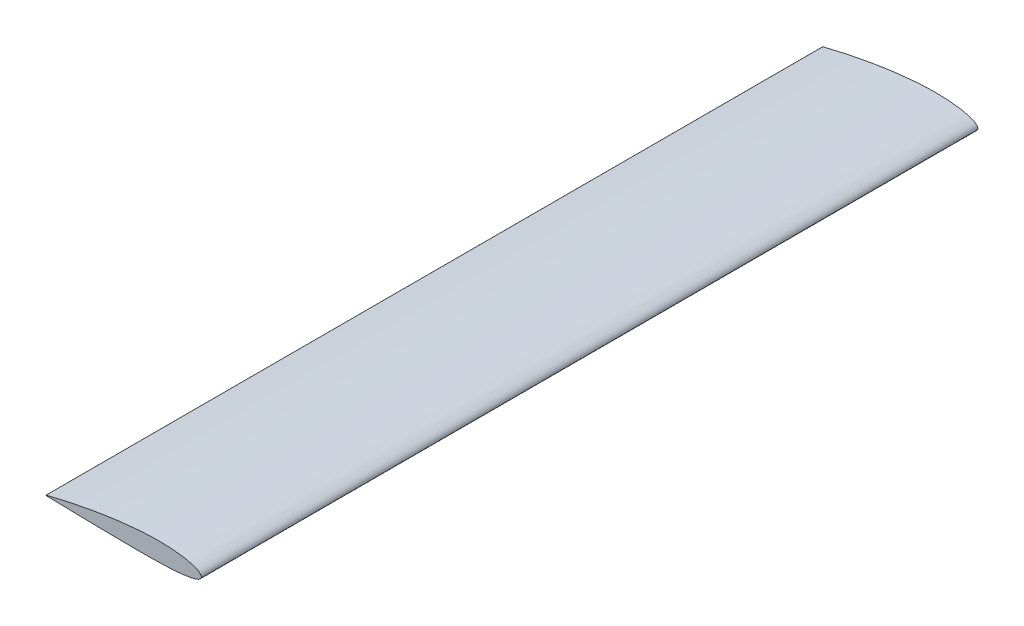
SolidWorks part; units mm, degrees
ref_plane "Front Plane" through (0, 0, 0) normal (0, 0, 1) x (1, 0, 0)
ref_plane "Top Plane" through (0, 0, 0) normal (0, 1, 0) x (1, 0, 0)
ref_plane "Right Plane" through (0, 0, 0) normal (1, 0, 0) x (0, 0, -1)
curve "Curve1"
  spline degree 3 poles (1, 0.0013, 0) (0.9833, 0.0047, 0) (0.9501, 0.0115, 0) (0.8835, 0.024, 0) (0.8002, 0.0379, 0) (0.7002, 0.0522, 0) (0.6002, 0.0641, 0) (0.5001, 0.0729, 0) (0.4001, 0.0788, 0) (0.3166, 0.0798, 0) (0.2499, 0.077, 0) (0.1999, 0.073, 0) (0.1498, 0.0666, 0) (0.108, 0.0587, 0) (0.0748, 0.0498, 0) (0.0496, 0.0416, 0) (0.0282, 0.0322, 0) (0.0098, 0.0207, 0) (-0.0063, 0.0009, 0) (0.0104, -0.0165, 0) (0.0285, -0.0245, 0) (0.0497, -0.0305, 0) (0.0749, -0.0348, 0) (0.1083, -0.0385, 0) (0.1499, -0.0414, 0) (0.2, -0.0425, 0) (0.25, -0.0424, 0) (0.3167, -0.0409, 0) (0.4, -0.0382, 0) (0.5, -0.0336, 0) (0.6, -0.0276, 0) (0.7, -0.0214, 0) (0.8, -0.0151, 0) (0.8833, -0.0093, 0) (0.95, -0.0048, 0) (0.9833, -0.0025, 0) (1, -0.0013, 0) knots 0 0 0 0 0.025012 0.049959 0.099673 0.149206 0.198581 0.247805 0.296917 0.345953 0.370492 0.395091 0.419815 0.444799 0.45749 0.470406 0.483879 0.491264 0.503459 0.513609 0.520451 0.533235 0.545691 0.558032 0.582609 0.607135 0.631652 0.656174 0.705234 0.75432 0.803437 0.852566 0.901701 0.950849 0.975423 1 1 1 1
sketch "Sketch2" plane through (17.4402, 0, 0) normal (0, 0, 1) x (1, 0, 0)
  arc A1 (-38.9552, 1.4929) -> (-38.9506, 1.389) centre (-38.942, 1.4414) ccw
  circle A2 centre (-9.5405, 3.4849) radius 0.8125
  spline S0 degree 3 poles (-38.9552, 1.4929) (-38.2955, 1.6584) (-36.9778, 1.9889) (-34.3381, 2.6041) (-31.0337, 3.3023) (-27.0617, 4.0491) (-23.0862, 4.7008) (-19.1035, 5.2248) (-15.1167, 5.636) (-11.7835, 5.8217) (-9.1134, 5.8277) (-7.1057, 5.7534) (-5.0914, 5.5848) (-3.4106, 5.3423) (-2.0659, 5.0436) (-1.0442, 4.7633) (-0.174, 4.4228) (0.5824, 3.9968) (1.2592, 3.2326) (0.6225, 2.5072) (-0.0862, 2.158) (-0.9256, 1.8797) (-1.9224, 1.6628) (-3.2503, 1.457) (-4.9109, 1.2706) (-6.9089, 1.1377) (-8.9078, 1.0568) (-11.5747, 0.9993) (-14.9101, 0.9597) (-18.9146, 0.9694) (-22.9203, 1.0343) (-26.9271, 1.1087) (-30.9348, 1.1861) (-34.2744, 1.2726) (-36.9465, 1.3352) (-38.2826, 1.3711) (-38.9506, 1.389) knots 0 0 0 0 0.025012 0.049959 0.099673 0.149206 0.198581 0.247805 0.296917 0.345953 0.370492 0.395091 0.419815 0.444799 0.45749 0.470406 0.483879 0.491264 0.503459 0.513609 0.520451 0.533235 0.545691 0.558032 0.582609 0.607135 0.631652 0.656174 0.705234 0.75432 0.803437 0.852566 0.901701 0.950849 0.975423 1 1 1 1
  dimension "D1" = 1.625
extrude "Boss-Extrude1" add sketch "Sketch2" along normal blind 200 contours S0 A1
